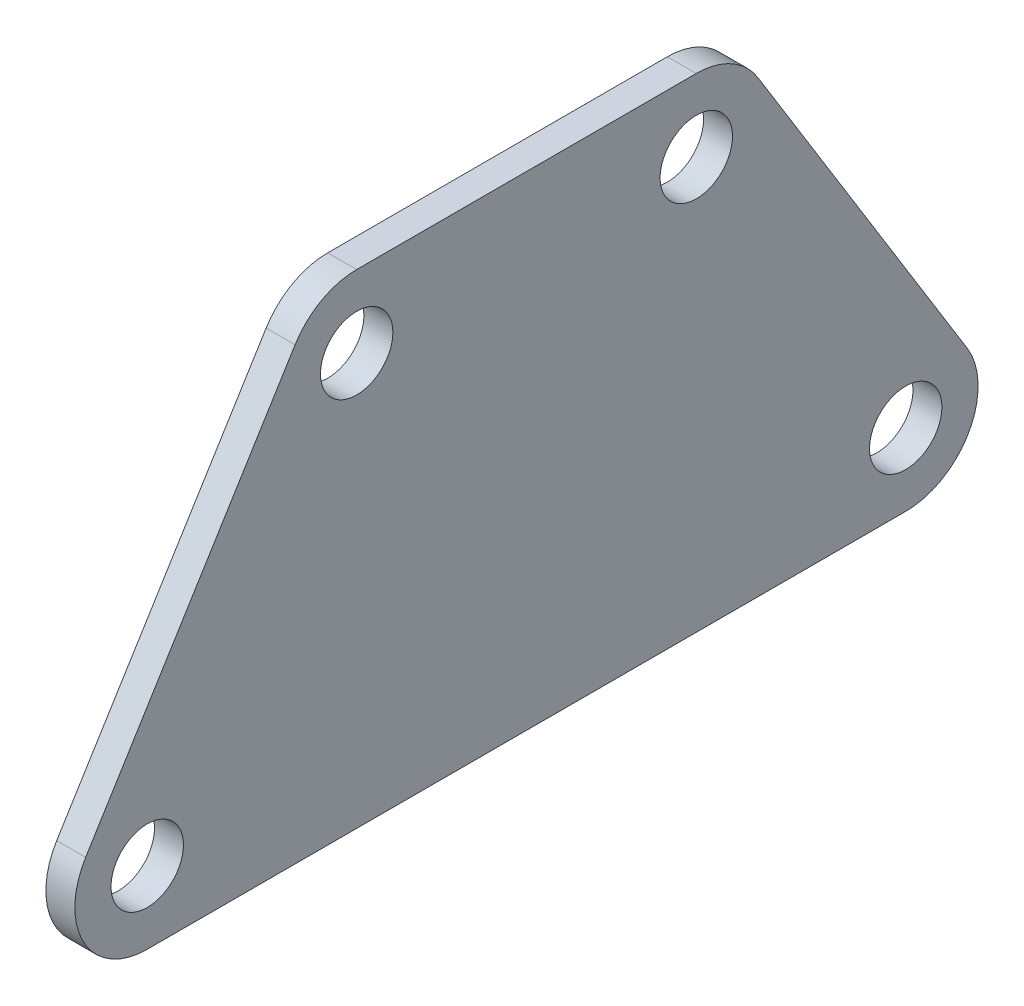
SolidWorks part; units mm, degrees
ref_plane "Front Plane" through (0, 0, 0) normal (0, 0, 1) x (1, 0, 0)
ref_plane "Top Plane" through (0, 0, 0) normal (0, 1, 0) x (1, 0, 0)
ref_plane "Right Plane" through (0, 0, 0) normal (1, 0, 0) x (0, 0, -1)
sketch "Sketch1" plane through (0, 0, 0) normal (1, 0, 0) x (0, 0, -1)
  line L0 (-36.6068, 46.1274) -> (10.3104, 46.1274)
  line L1 (18.8193, 41.3807) -> (47.7473, -5.474)
  line L2 (39.2383, -20.7274) -> (-65.5347, -20.7274)
  line L3 (-74.0437, -5.474) -> (-45.1157, 41.3807)
  arc A0 (47.7473, -5.474) -> (39.2383, -20.7274) centre (39.2383, -10.7274) cw
  arc A1 (10.3104, 46.1274) -> (18.8193, 41.3807) centre (10.3104, 36.1274) cw
  arc A2 (-36.6068, 46.1274) -> (-45.1157, 41.3807) centre (-36.6068, 36.1274) ccw
  arc A3 (-74.0437, -5.474) -> (-65.5347, -20.7274) centre (-65.5347, -10.7274) ccw
  circle A4 centre (-36.6068, 36.1274) radius 5
  circle A5 centre (10.3104, 36.1274) radius 5
  circle A6 centre (39.2383, -10.7274) radius 5
  circle A7 centre (-65.5347, -10.7274) radius 5
  dimension "D1" = 10
extrude "Boss-Extrude1" add sketch "Sketch1" along normal blind 4
